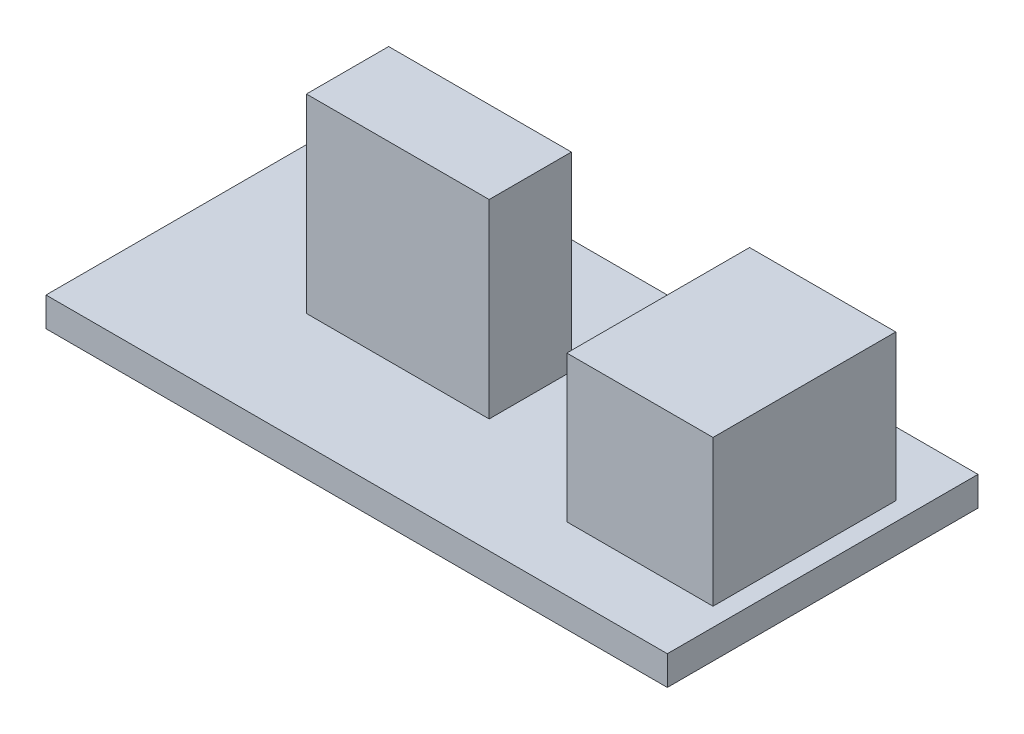
SolidWorks part; units mm, degrees
ref_plane "Front Plane" through (0, 0, 0) normal (0, 0, 1) x (1, 0, 0)
ref_plane "Top Plane" through (0, 0, 0) normal (0, 1, 0) x (1, 0, 0)
ref_plane "Right Plane" through (0, 0, 0) normal (1, 0, 0) x (0, 0, -1)
other "Configuration Table"
sketch "Sketch1" plane through (0, 0, 0) normal (0, 1, 0) x (1, 0, 0)
  line L1 (-17, -8.5) -> (17, -8.5)
  line L2 (-17, -8.5) -> (-17, 8.5)
  line L3 (-17, 8.5) -> (17, 8.5)
  line L4 (17, -8.5) -> (17, 8.5)
  line L5 (-17, -8.5) -> (17, 8.5) construction
  line L6 (-17, 8.5) -> (17, -8.5) construction
  point P6 (0, 0)
  dimension "D1" = 34
  dimension "D2" = 17
extrude "Board" add sketch "Sketch1" along normal blind 1.6
sketch "Sketch2" plane through (0, 0, 0) normal (0, 1, 0) x (1, 0, 0)
  line L0 (-9, -2.25) -> (1, -2.25)
  line L1 (1, -2.25) -> (1, 2.25)
  line L2 (1, 2.25) -> (-9, 2.25)
  line L3 (-9, 2.25) -> (-9, -2.25)
extrude "TO220" add sketch "Sketch2" along normal blind 10.4 from offset 1.6
sketch "Sketch3" plane through (0, 0, 0) normal (0, 1, 0) x (1, 0, 0)
  line L0 (8, -5) -> (16, -5)
  line L1 (16, -5) -> (16, 5)
  line L2 (16, 5) -> (8, 5)
  line L3 (8, 5) -> (8, -5)
extrude "Terminal_Block" add sketch "Sketch3" along normal blind 8 from offset 1.6
equation "\"Jar_OD\"= 90  'ASSUMED - Part G fallback - jar outer diameter"
equation "\"Jar_H\"= 120  'ASSUMED - Part G fallback - jar height"
equation "\"Pump_L\"= 45  'ASSUMED - Part G fallback"
equation "\"Pump_W\"= 24  'ASSUMED - Part G fallback"
equation "\"Pump_H\"= 33  'ASSUMED - Part G fallback"
equation "\"Pump_Outlet_OD\"= 7.5  'ASSUMED - Part G fallback"
equation "\"Tube_OD\"= 8  'ASSUMED - Part G fallback"
equation "\"Tube_ID\"= 6  'ASSUMED - Part G fallback"
equation "\"TDS_Body_Dia\"= 12  'ASSUMED - Part G fallback"
equation "\"TDS_Wet_Len\"= 45  'ASSUMED - Part G fallback - length in water"
equation "\"DS_Tube_Dia\"= 6  'ASSUMED - Part G fallback"
equation "\"DS_Tube_Len\"= 50  'ASSUMED - Part G fallback"
equation "\"ORP_Body_Dia\"= 12  'ASSUMED - Part G fallback"
equation "\"ORP_Body_Len\"= 150  'ASSUMED - Part G fallback"
equation "\"ORP_Cap_Dia\"= 16  'ASSUMED - Part G fallback"
equation "\"Turb_W\"= 33  'ASSUMED - Part G fallback - head width"
equation "\"Turb_D\"= 28  'ASSUMED - Part G fallback - head depth"
equation "\"Turb_H\"= 30  'ASSUMED - Part G fallback - head height"
equation "\"Turb_Slot_W\"= 10  'ASSUMED - Part G fallback - slot width"
equation "\"Flow_L\"= 62  'ASSUMED - Part G fallback YF-S201"
equation "\"Flow_W\"= 36  'ASSUMED - Part G fallback"
equation "\"Flow_H\"= 35  'ASSUMED - Part G fallback"
equation "\"Thread_G12_OD\"= 20.955  'ASSUMED - Part G fallback thread G1/2 (major diameter)"
equation "\"Valve_L\"= 75  'ASSUMED - Part G fallback"
equation "\"Valve_W\"= 45  'ASSUMED - Part G fallback"
equation "\"Valve_H\"= 60  'ASSUMED - Part G fallback"
equation "\"Tee_L\"= 40  'ASSUMED - Part G fallback - overall length"
equation "\"Tee_Branch_L\"= 25  'ASSUMED - Part G fallback"
equation "\"Tee_OD\"= 12  'ASSUMED - Part G fallback"
equation "\"Cuv_W\"= 12.5  'ASSUMED - old R3 cuvette (station suppressed in SS4)"
equation "\"Cuv_D\"= 12.5  'ASSUMED - old R3 cuvette (station suppressed in SS4)"
equation "\"Cuv_H\"= 45  'ASSUMED - old R3 cuvette (station suppressed in SS4)"
equation "\"LED_Board_L\"= 20  'ASSUMED - Part G fallback"
equation "\"LED_Board_W\"= 20  'ASSUMED - Part G fallback - LED at centre"
equation "\"GUVA_L\"= 20  'ASSUMED - Part G fallback"
equation "\"GUVA_W\"= 12  'ASSUMED - Part G fallback - sensor at centre"
equation "\"Reed_L\"= 27  'ASSUMED - Part G fallback MC-38 half"
equation "\"Reed_W\"= 14  'ASSUMED - Part G fallback"
equation "\"Reed_H\"= 8  'ASSUMED - Part G fallback"
equation "\"ESP_L\"= 51  'ASSUMED - Part G fallback"
equation "\"ESP_W\"= 28  'ASSUMED - Part G fallback"
equation "\"TFT_L\"= 58  'ASSUMED - Part G fallback - board"
equation "\"TFT_W\"= 35  'ASSUMED - Part G fallback - board"
equation "\"TFT_Win_L\"= 35  'ASSUMED - Part G fallback - visible window"
equation "\"TFT_Win_W\"= 28  'ASSUMED - Part G fallback - visible window"
equation "\"Relay_L\"= 50  'ASSUMED - Part G fallback"
equation "\"Relay_W\"= 26  'ASSUMED - Part G fallback"
equation "\"Relay_H\"= 19  'ASSUMED - Part G fallback"
equation "\"Mosfet_L\"= 34  'ASSUMED - Part G fallback"
equation "\"Mosfet_W\"= 17  'ASSUMED - Part G fallback"
equation "\"Mosfet_H\"= 12  'ASSUMED - Part G fallback"
equation "\"TDS_Board_L\"= 42  'ASSUMED - Part G fallback"
equation "\"TDS_Board_W\"= 32  'ASSUMED - Part G fallback"
equation "\"Turb_Board_L\"= 38  'ASSUMED - Part G fallback"
equation "\"Turb_Board_W\"= 28  'ASSUMED - Part G fallback"
equation "\"BNC_Thread_Dia\"= 9.5  'ASSUMED - Part G fallback"
equation "\"Plate_L\"= 420  'ASSUMED - Part G fallback"
equation "\"Plate_W\"= 297  'ASSUMED - Part G fallback"
equation "\"Plate_T\"= 6  'ASSUMED - Part G fallback"
equation "\"Probe_Clr\"= 0.3  'DESIGN VALUE - Part C rule 3 - printed probe hole = diameter + 0.3"
equation "\"Cuv_Clr\"= 0.2  'DESIGN VALUE - Part C rule 3 - cuvette pocket = size + 0.2"
equation "\"Label_H\"= 0.6  'DESIGN VALUE - Part D - raised label height"
equation "\"D1@Sketch1\" = \"Mosfet_L\""
equation "\"D2@Sketch1\" = \"Mosfet_W\""
equation "\"Booster_L\"= 150  'ASSUMED - Part G fallback - booster pump"
equation "\"Booster_W\"= 95  'ASSUMED - Part G fallback"
equation "\"Booster_H\"= 100  'ASSUMED - Part G fallback"
equation "\"PTube_OD\"= 6.35  'ASSUMED - Part G fallback - product tube 1/4 inch"
equation "\"Qz_Out\"= 12  'ASSUMED - Part G fallback - quartz channel outside square"
equation "\"Qz_Path\"= 10  'ASSUMED - Part G fallback - quartz channel inside light path"
equation "\"Qz_L\"= 40  'ASSUMED - Part G fallback - quartz channel length"
equation "\"LED860_Dia\"= 5  'ASSUMED - Part G fallback - 860 nm LED"
equation "\"BPW_L\"= 5.4  'ASSUMED - Part G fallback - BPW34"
equation "\"BPW_W\"= 4.3  'ASSUMED - Part G fallback - BPW34"
equation "\"Cart_Dia\"= 50  'ASSUMED - Part G fallback - sediment and pre-carbon cartridges"
equation "\"Cart_L\"= 255  'ASSUMED - Part G fallback"
equation "\"UF_Dia\"= 50  'ASSUMED - Part G fallback - UF cartridge"
equation "\"UF_L\"= 260  'ASSUMED - Part G fallback"
equation "\"RO_Dia\"= 62  'ASSUMED - Part G fallback - RO membrane housing"
equation "\"RO_L\"= 300  'ASSUMED - Part G fallback"
equation "\"UVC_Dia\"= 40  'ASSUMED - Part G fallback - UV-C chamber"
equation "\"UVC_L\"= 300  'ASSUMED - Part G fallback"
equation "\"Tank_W\"= 260  'ASSUMED - Part G fallback - storage tank"
equation "\"Tank_D\"= 160  'ASSUMED - Part G fallback"
equation "\"Tank_H\"= 300  'ASSUMED - Part G fallback"
equation "\"Cab_W\"= 400  'ASSUMED - Part G fallback - purifier cabinet"
equation "\"Cab_D\"= 270  'ASSUMED - Part G fallback"
equation "\"Cab_H\"= 560  'ASSUMED - Part G fallback"
equation "\"ORP_Board_L\"= 40  'ASSUMED - Part G fallback - ORP buffer board"
equation "\"ORP_Board_W\"= 30  'ASSUMED - Part G fallback"
equation "\"Opt_Board_L\"= 50  'ASSUMED - Part G fallback - optical front-end board"
equation "\"Opt_Board_W\"= 40  'ASSUMED - Part G fallback"
equation "\"Buck_L\"= 43  'ASSUMED - Part G fallback - 12 V to 5 V buck module"
equation "\"Buck_W\"= 21  'ASSUMED - Part G fallback"
equation "\"Buck_H\"= 14  'ASSUMED - Part G fallback"
equation "\"BB_L\"= 165  'ASSUMED - Part G fallback - breadboard (As_Built_R3 only)"
equation "\"BB_W\"= 55  'ASSUMED - Part G fallback"
equation "\"BB_H\"= 10  'ASSUMED - Part G fallback"
